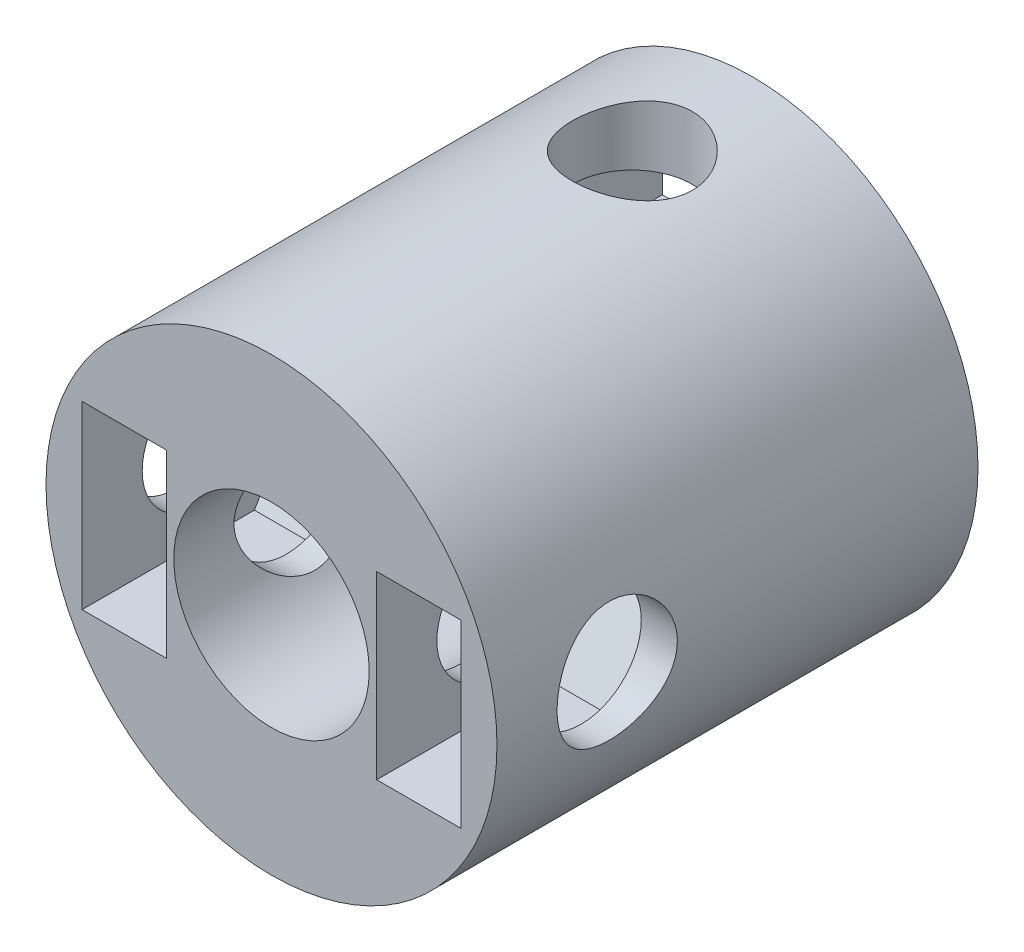
SolidWorks part; units mm, degrees
ref_plane "Front Plane" through (0, 0, 0) normal (0, 0, 1) x (1, 0, 0)
ref_plane "Top Plane" through (0, 0, 0) normal (0, 1, 0) x (1, 0, 0)
ref_plane "Right Plane" through (0, 0, 0) normal (1, 0, 0) x (0, 0, -1)
sketch "Sketch2" plane through (0, 0, 0) normal (1, 0, 0) x (0, 0, -1)
  line L0 (-33.3264, 0) -> (52.37, 0) construction
  line L1 (8, 2.25) -> (0, 2.25)
  line L2 (0, 2.25) -> (0, 3.25)
  line L3 (0, 3.25) -> (-8, 3.25)
  line L4 (-8, 3.25) -> (-8, 7.5)
  line L5 (-8, 7.5) -> (8, 7.5)
  line L6 (8, 7.5) -> (8, 2.25)
  line L7 (0, 10.6921) -> (0, -5.6685) construction
  dimension "D1" = 2.25
  dimension "D2" = 3.25
  dimension "D3" = 16
  dimension "D4" = 7.5
revolve "Revolve1" add sketch "Sketch2" angle 360 about L0
sketch "Sketch4" plane through (0, 0, 0) normal (0, 1, 0) x (1, 0, 0)
  line L2 (3.9503, 4) -> (-3.9111, 4) construction
  line L3 (-3.25, 0) -> (3.25, 0) construction
  line L4 (2.25, 8) -> (-2.25, 8) construction
  circle A0 centre (0, 4) radius 2
  dimension "D1" = 4
extrude "Cut-Extrude1" cut sketch "Sketch4" against normal through all and the other way through all
sketch "Sketch5" plane through (0, 0, 0) normal (1, 0, 0) x (0, 0, -1)
  line L0 (-8, 0) -> (0, 0) construction
  line L1 (-8, 3.25) -> (-8, -3.25) construction
  line L2 (0, 3.25) -> (0, -3.25) construction
  circle A0 centre (-4, 0) radius 2
  dimension "D1" = 4
extrude "Cut-Extrude2" cut sketch "Sketch5" against normal through all and the other way through all
ref_plane "Nut Plane 6mm Right" through (4.9, 0, 0) normal (1, 0, 0) x (0, 0, -1)
sketch "Sketch6" plane through (4.9, 0, 0) normal (1, 0, 0) x (0, 0, -1)
  line L0 (-5.7321, 3) -> (-8, 3)
  line L1 (-7.4641, 0) -> (-5.7321, -3) construction
  line L2 (-5.7321, -3) -> (-2.2679, -3)
  line L3 (-2.2679, -3) -> (-0.5359, 0)
  line L4 (-0.5359, 0) -> (-2.2679, 3)
  line L5 (-2.2679, 3) -> (-5.7321, 3)
  line L6 (-5.7321, 3) -> (-7.4641, 0) construction
  line L7 (-8, 3) -> (-8, -3)
  line L8 (-8, -3) -> (-5.7321, -3)
  line L9 (-8, 7.5) -> (-8, -7.5) construction
  circle A0 centre (-4, 0) radius 3 construction
  dimension "D1" = 6
extrude "Cut-Extrude3" cut sketch "Sketch6" against normal mid plane 2.8
ref_plane "Nut Plane 6mm Left" through (-4.9, 0, 0) normal (1, 0, 0) x (0, 0, -1)
sketch "Sketch7" plane through (-4.9, 0, 0) normal (1, 0, 0) x (0, 0, -1)
  line L0 (-5.7321, 3) -> (-8, 3)
  line L1 (-7.4641, 0) -> (-5.7321, -3) construction
  line L2 (-5.7321, -3) -> (-2.2679, -3)
  line L3 (-2.2679, -3) -> (-0.5359, 0)
  line L4 (-0.5359, 0) -> (-2.2679, 3)
  line L5 (-2.2679, 3) -> (-5.7321, 3)
  line L6 (-5.7321, 3) -> (-7.4641, 0) construction
  line L7 (-8, 3) -> (-8, -3)
  line L8 (-8, -3) -> (-5.7321, -3)
  line L10 (-8, 7.5) -> (-8, -7.5) construction
  circle A0 centre (-4, 0) radius 3 construction
  circle A1 centre (-4, 0) radius 2 construction
  dimension "D1" = 6
extrude "Cut-Extrude4" cut sketch "Sketch7" against normal mid plane 2.8
ref_plane "Nut Plane 4mm Top" through (0, 4, 0) normal (0, 1, 0) x (-1, 0, 0)
sketch "Sketch8" plane through (0, 4, 0) normal (0, 1, 0) x (-1, 0, 0)
  line L0 (3, -5.7321) -> (3, -8)
  line L1 (0, -0.5359) -> (-3, -2.2679)
  line L2 (-3, -2.2679) -> (-3, -5.7321)
  line L3 (-3, -5.7321) -> (0, -7.4641) construction
  line L4 (0, -7.4641) -> (3, -5.7321) construction
  line L5 (3, -5.7321) -> (3, -2.2679)
  line L6 (3, -2.2679) -> (0, -0.5359)
  line L7 (-7.5, -8) -> (7.5, -8) construction
  line L8 (3, -8) -> (-3, -8)
  line L9 (-3, -8) -> (-3, -5.7321)
  circle A0 centre (0, -4) radius 3 construction
  dimension "D1" = 6
extrude "Cut-Extrude5" cut sketch "Sketch8" against normal mid plane 2.8
ref_plane "Plane4" through (0, -4, 0) normal (0, 1, 0) x (-1, 0, 0)
sketch "Sketch9" plane through (0, -4, 0) normal (0, 1, 0) x (-1, 0, 0)
  line L0 (-3, -5.7321) -> (-3, -8)
  line L1 (0, -7.4641) -> (3, -5.7321) construction
  line L2 (3, -5.7321) -> (3, -2.2679)
  line L3 (3, -2.2679) -> (0, -0.5359)
  line L4 (0, -0.5359) -> (-3, -2.2679)
  line L5 (-3, -2.2679) -> (-3, -5.7321)
  line L6 (-3, -5.7321) -> (0, -7.4641) construction
  line L7 (-3, -8) -> (3, -8)
  line L8 (3, -8) -> (3, -5.7321)
  line L9 (-7.5, -8) -> (7.5, -8) construction
  circle A0 centre (0, -4) radius 3 construction
  dimension "D1" = 6
extrude "Cut-Extrude6" cut sketch "Sketch9" against normal mid plane 2.8
